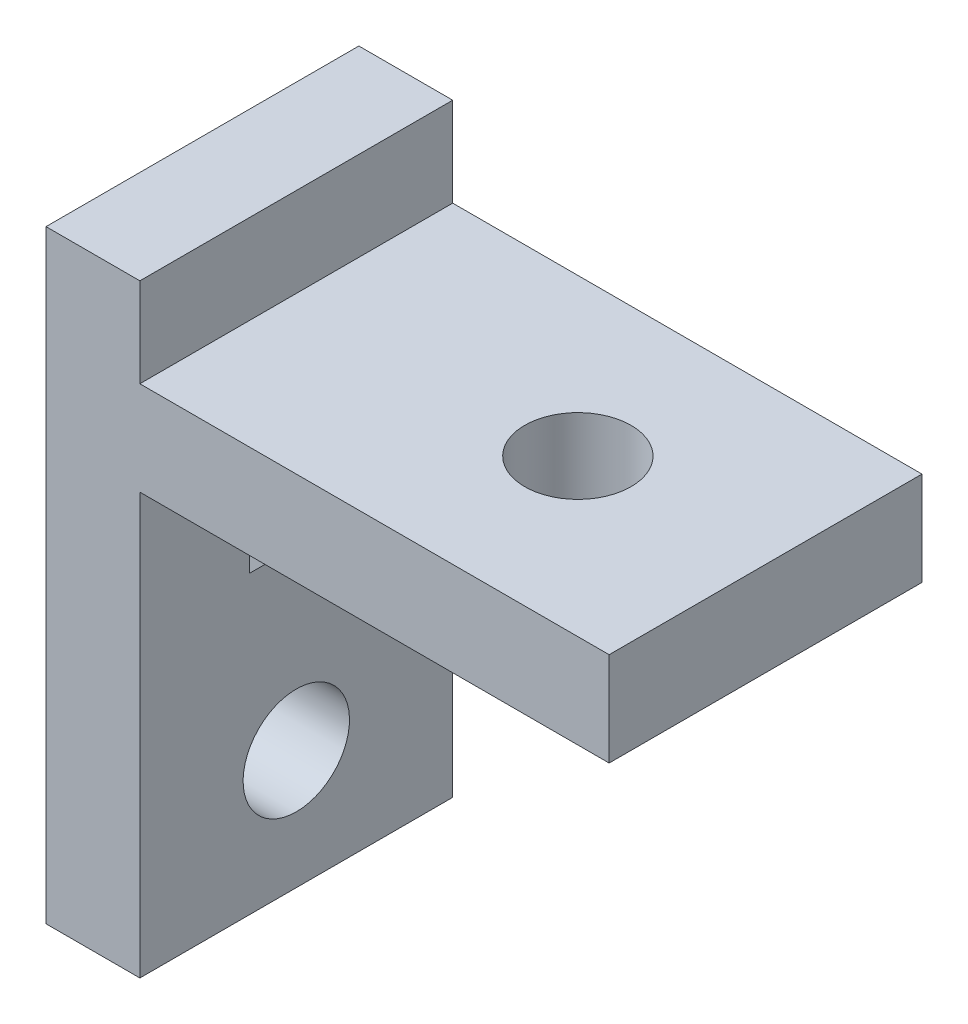
SolidWorks part; units mm, degrees
ref_plane "Front" through (0, 0, 0) normal (0, 0, 1) x (1, 0, 0)
ref_plane "Top" through (0, 0, 0) normal (0, 1, 0) x (1, 0, 0)
ref_plane "Right" through (0, 0, 0) normal (1, 0, 0) x (0, 0, -1)
sketch "Sketch1" plane through (0, 0, 0) normal (0, 0, 1) x (1, 0, 0)
  line L0 (0, 0) -> (3, 0)
  line L1 (3, 0) -> (3, 13.45)
  line L2 (18, 16.45) -> (0, 16.45)
  line L3 (0, 16.45) -> (0, 0)
  line L4 (3, 13.45) -> (18, 13.45)
  line L5 (18, 13.45) -> (18, 16.45)
  dimension "D1" = 18
  dimension "D2" = 16.45
  dimension "D3" = 3
extrude "Boss-Extrude1" add sketch "Sketch1" along normal mid plane 10
sketch "Sketch2" plane through (0, 0, 0) normal (-1, 0, 0) x (0, 0, 1)
  line L0 (0, 3.8) -> (0, 0) construction
  line L1 (5, 0) -> (-5, 0) construction
  circle A0 centre (0, 3.8) radius 1.7
  dimension "D1" = 3.4
  dimension "D2" = 3.8
extrude "Cut-Extrude1" cut sketch "Sketch2" against normal through all
sketch "Sketch3" plane through (0, 13.45, 0) normal (0, -1, 0) x (1, 0, 0)
  line L0 (12, 0) -> (18, 0) construction
  line L1 (18, 5) -> (18, -5) construction
  line L2 (0, 5) -> (0, -5) construction
  circle A0 centre (12, 0) radius 1.7
  dimension "D1" = 3.4
  dimension "D2" = 12
extrude "Cut-Extrude2" cut sketch "Sketch3" against normal through all
sketch "Sketch5" plane through (0, 0, 5) normal (0, 0, 1) x (1, 0, 0)
  line L0 (3, 0) -> (3, 13.45) construction
  line L1 (0, 16.45) -> (3, 16.45)
  line L2 (0, 16.45) -> (0, 19.3)
  line L3 (0, 19.3) -> (3, 19.3)
  line L4 (3, 16.45) -> (3, 19.3)
  dimension "D1" = 2.85
extrude "Boss-Extrude2" add sketch "Sketch5" against normal up to surface (10 mm away) up to face at (7, 9.9667, -5)
sketch "Sketch6" plane through (0, 0, 0) normal (0, 0, 1) x (1, 0, 0)
  line L0 (7, 13.45) -> (3, 9.45)
  line L1 (3, 13.45) -> (18, 13.45) construction
  line L2 (3, 0) -> (3, 13.45) construction
  line L3 (3, 9.45) -> (3, 13.45)
  line L4 (3, 13.45) -> (7, 13.45)
  dimension "D1" = 4
extrude "Boss-Extrude3" add sketch "Sketch6" along normal mid plane 3
